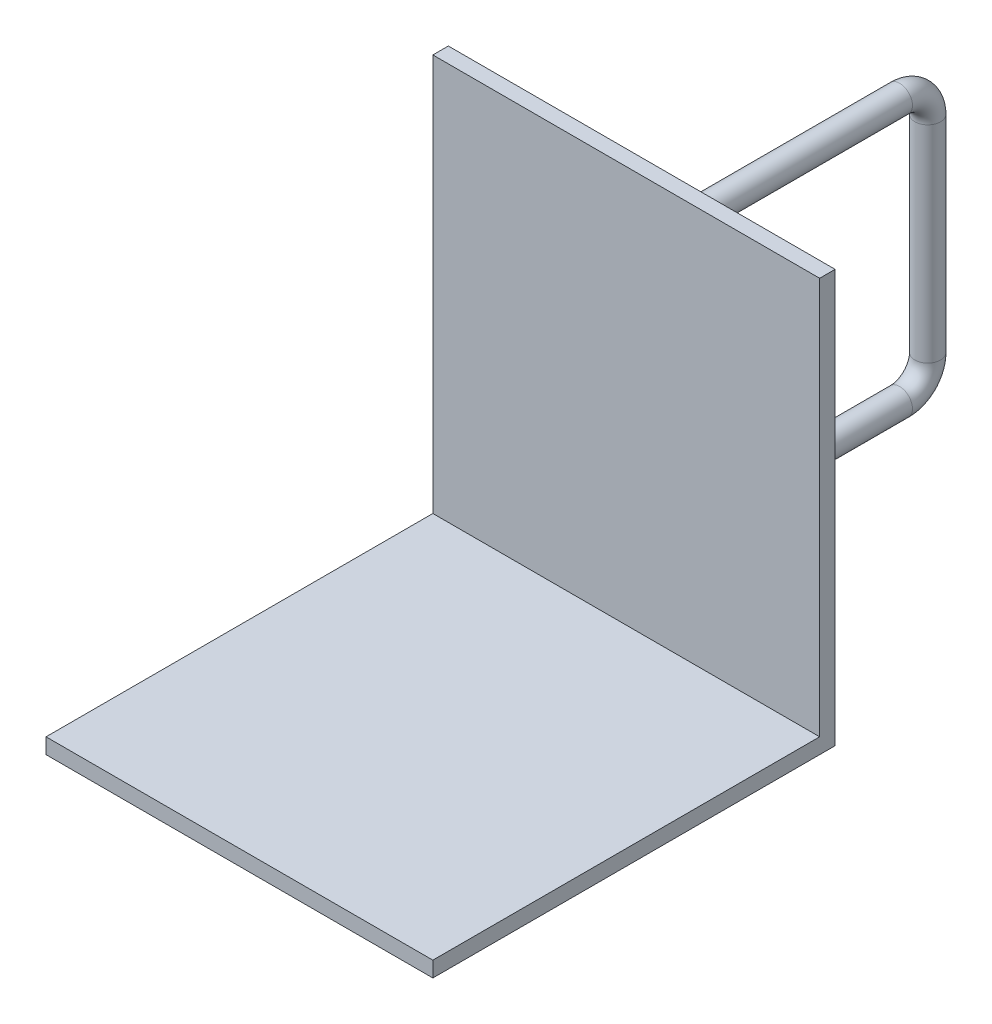
SolidWorks part; units mm, degrees
ref_plane "Front Plane" through (0, 0, 0) normal (0, 0, 1) x (1, 0, 0)
ref_plane "Top Plane" through (0, 0, 0) normal (0, 1, 0) x (1, 0, 0)
ref_plane "Right Plane" through (0, 0, 0) normal (1, 0, 0) x (0, 0, -1)
sketch "Sketch1" plane through (0, 0, 0) normal (0, 0, 1) x (1, 0, 0)
  line L1 (0, 0) -> (-75, 0)
  line L2 (0, 0) -> (0, 80)
  line L3 (0, 80) -> (-75, 80)
  line L4 (-75, 0) -> (-75, 80)
  dimension "D1" = 75
  dimension "D2" = 80
extrude "Boss-Extrude1" add sketch "Sketch1" along normal blind 3
sketch "Sketch2" plane through (0, 0, 3) normal (0, 0, 1) x (1, 0, 0)
  line L1 (0, 0) -> (-75, 0)
  line L2 (0, 0) -> (0, 3)
  line L3 (0, 3) -> (-75, 3)
  line L4 (-75, 0) -> (-75, 3)
  dimension "D1" = 75
  dimension "D2" = 3
extrude "Boss-Extrude2" add sketch "Sketch2" along normal blind 75
sketch "Sketch5" plane through (0, 0, 3) normal (0, 0, 1) x (1, 0, 0)
  line L0 (-37.5, 3) -> (-37.5, 80) construction
  line L1 (0, 3) -> (-75, 3) construction
  line L2 (0, 80) -> (-75, 80) construction
  circle A0 centre (-37.5, 65) radius 2.5
  dimension "D1" = 5
  dimension "D4" = 15
extrude "Boss-Extrude3" add sketch "Sketch5" against normal blind 3.1
sketch "Sketch7" plane through (0, 0, 0) normal (1, 0, 0) x (0, 0, -1)
  line L0 (0, 64.5414) -> (50, 64.5414)
  line L1 (0, 0) -> (0, 80) construction
  line L2 (55, 59.5414) -> (55, 19.5414)
  line L3 (50, 14.5414) -> (0, 14.5414)
  arc A0 (55, 19.5414) -> (50, 14.5414) centre (50, 19.5414) cw
  arc A1 (55, 59.5414) -> (50, 64.5414) centre (50, 59.5414) ccw
  point P8 (55, 14.5414)
  point P11 (55, 64.5414)
  dimension "D3" = 5
  dimension "D1" = 55
  dimension "D2" = 50
sketch "Sketch8" plane through (0, 0, -0.1) normal (0, 0, -1) x (-1, 0, 0)
  circle A0 centre (37.5, 65) radius 2.5
sweep "Sweep1" add profiles "Sketch8" path "Sketch7"
